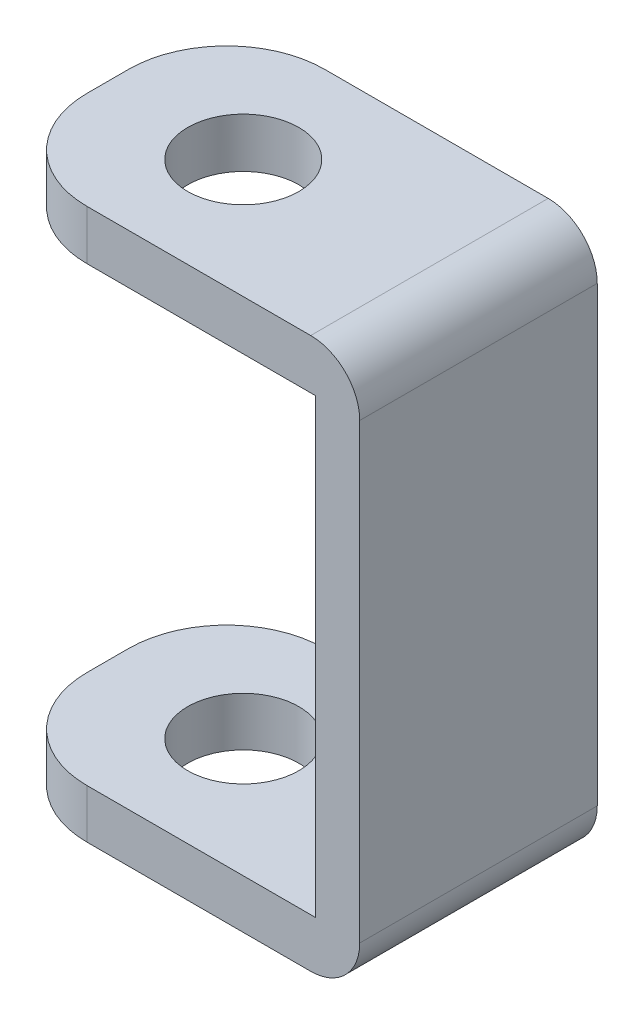
SolidWorks part; units mm, degrees
material "Galvanized Steel"
ref_plane "Front Plane" through (0, 0, 0) normal (0, 0, 1) x (1, 0, 0)
ref_plane "Top Plane" through (0, 0, 0) normal (0, 1, 0) x (1, 0, 0)
ref_plane "Right Plane" through (0, 0, 0) normal (1, 0, 0) x (0, 0, -1)
sketch "Sketch2" plane through (0, 0, 0) normal (0, 1, 0) x (1, 0, 0)
  line L0 (-0.1213, 14) -> (-0.1213, 19.9)
  line L1 (52.7787, 33.9) -> (52.7787, 0)
  line L2 (13.8787, 0) -> (52.7787, 0)
  line L4 (-0.1213, 0) -> (0.1765, -0.305)
  line L6 (13.8787, 33.9) -> (52.7787, 33.9)
  arc A0 (-0.1213, 19.9) -> (13.8787, 33.9) centre (13.8787, 19.9) cw
  arc A1 (-0.1213, 14) -> (13.8787, 0) centre (13.8787, 14) ccw
  circle A2 centre (19.2057, 16.95) radius 7.93
  point P10 (-0.1213, 33.9)
  dimension "D1" = 14
  dimension "D2" = 52.9
  dimension "D3" = 33.9
extrude "Boss-Extrude1" add sketch "Sketch2" along normal blind 78.59 contours L0 A1 L2 L1 L6 A0 A2
fillet "Fillet1" radius 7 1 edges at (52.7787, 78.59, -16.95)
sketch "Sketch8" plane through (0, 0, 0) normal (0, 0, 1) x (1, 0, 0)
  line L1 (46.4455, 69.59) -> (46.4455, 7)
  line L2 (46.4455, 38.295) -> (46.3899, 38.2508)
  line L3 (13.8787, 71.5002) -> (46.4455, 71.5002)
  line L4 (46.4455, 71.5002) -> (46.4455, 69.59)
  line L5 (13.8787, 71.5002) -> (-13.3064, 71.5002)
  line L6 (-13.3064, 69.59) -> (-13.3064, 7)
  line L7 (-13.3064, 7) -> (13.8787, 7)
  line L8 (-13.3064, 71.5002) -> (-13.3064, 69.59)
  line L10 (46.4455, 7) -> (13.8787, 7)
extrude "Cut-Extrude1" cut sketch "Sketch8" against normal blind 86.59
fillet "Fillet2" radius 7 1 edges at (52.7787, 0, -16.95)
